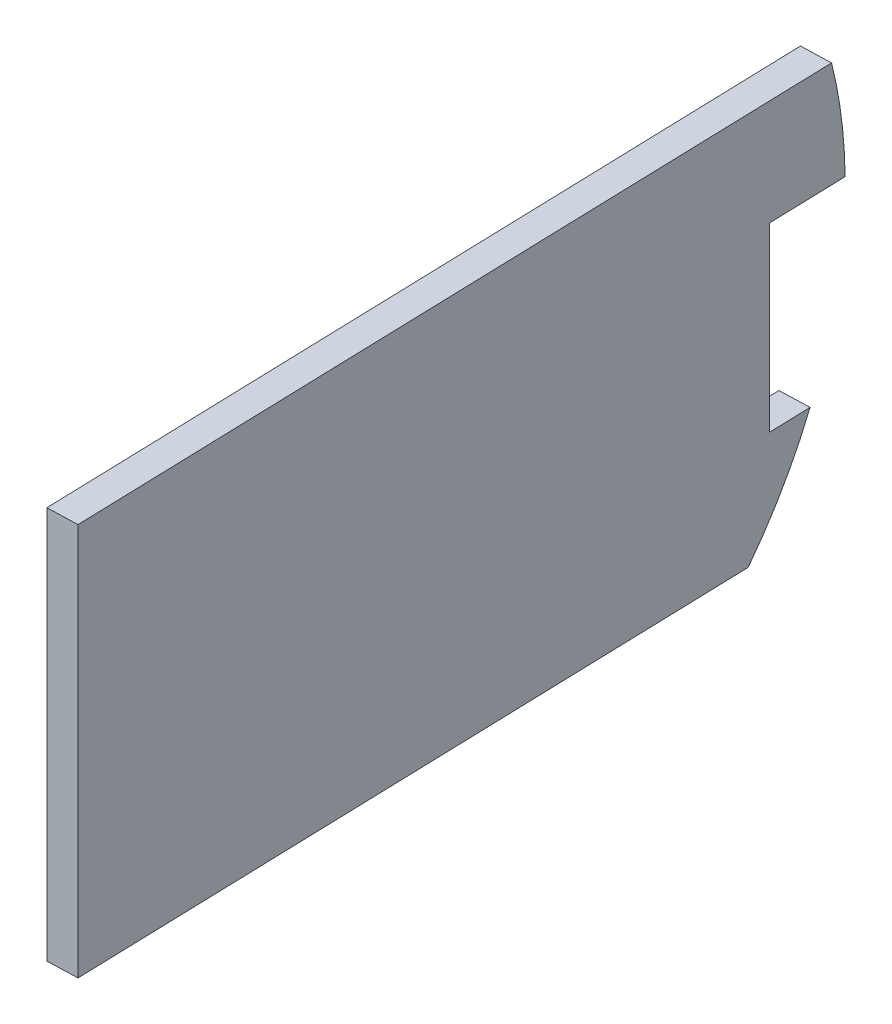
SolidWorks part; units mm, degrees
ref_plane "Alzado" through (0, 0, 0) normal (0, 0, 1) x (1, 0, 0)
ref_plane "Planta" through (0, 0, 0) normal (0, 1, 0) x (1, 0, 0)
ref_plane "Vista lateral" through (0, 0, 0) normal (1, 0, 0) x (0, 0, -1)
sketch "Croquis2" plane through (2.4903, 0, -0.0739) normal (0.9996, 0, -0.0297) x (-0.0297, 0, -0.9996)
  line L1 (-0.3266, 53.3031) -> (116.8859, 53.3031)
  line L2 (-0.3266, 53.3031) -> (-0.3266, -11.6969)
  line L3 (-0.3266, -11.6969) -> (114.0593, -11.6969)
  line L5 (116.8859, 53.3031) -> (128.2999, 53.3031)
  arc A0 (128.2999, 53.3031) -> (114.0593, -11.6969) centre (56.6122, 34.9489) cw
extrude "Saliente-Extruir2" add sketch "Croquis2" against normal blind 5
sketch "Croquis3" plane through (2.4903, 0, -0.0739) normal (0.9996, 0, -0.0297) x (-0.0297, 0, -0.9996)
  line L0 (-0.3266, 53.3031) -> (-0.3266, -11.6969) construction
  line L6 (132.6864, 35.8031) -> (117.6864, 35.8031)
  line L7 (132.6864, 35.8031) -> (132.6864, 5.8031)
  line L8 (132.6864, 5.8031) -> (117.6864, 5.8031)
  line L9 (117.6864, 35.8031) -> (117.6864, 5.8031)
  point P4 (117.6864, 20.8031)
  point P10 (-0.3266, 20.8031)
  dimension "D1" = 15
  dimension "D2" = 30
  dimension "D3" = 0
extrude "Cortar-Extruir2" cut sketch "Croquis3" against normal blind 10 contours L6 L9 L8 L7
